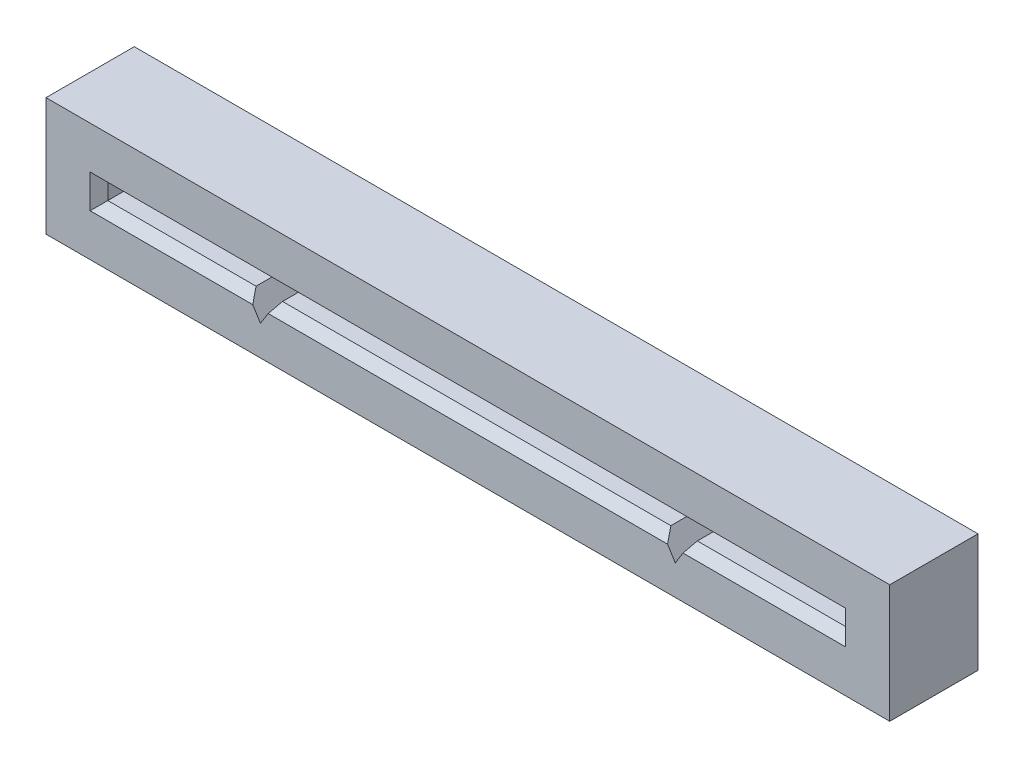
SolidWorks part; units mm, degrees
material "Сосна"
ref_plane "Front" through (0, 0, 0) normal (0, 0, 1) x (1, 0, 0)
ref_plane "Top" through (0, 0, 0) normal (0, 1, 0) x (1, 0, 0)
ref_plane "Right" through (0, 0, 0) normal (1, 0, 0) x (0, 0, -1)
sketch "Эскиз1" plane through (0, 66.7543, 0) normal (0, 0, 1) x (-1, 0, 0)
  line L1 (23.9, 63.4043) -> (-23.9, 70.1043) construction
  line L31 (-23.9, 63.4043) -> (23.9, 63.4043)
  line L32 (-23.9, 63.4043) -> (-23.9, 70.1043)
  line L33 (-23.9, 70.1043) -> (23.9, 70.1043)
  line L34 (23.9, 63.4043) -> (23.9, 70.1043)
  line L35 (-23.9, 63.4043) -> (23.9, 70.1043) construction
  point P12 (0, 66.7543)
  point P22 (0, 66.7543)
  point P26 (0, 66.7543)
  dimension "D1" = 6.7
  dimension "D2" = 47.8
extrude "Бобышка-Вытянуть1" add sketch "Эскиз1" along normal blind 5
sketch "Эскиз6" plane through (0, 66.7543, 5) normal (0, 0, 1) x (-1, 0, 0)
  line L0 (0, 66.3043) -> (0, 67.2043) construction
  line L1 (-20.9, 67.2043) -> (-12.5, 67.2043)
  line L4 (-20.9, 67.2043) -> (-20.9, 66.3043)
  line L5 (-20.9, 66.3043) -> (20.9, 66.3043)
  line L6 (20.9, 67.2043) -> (20.9, 66.3043)
  line L7 (-20.9, 67.2043) -> (20.9, 66.3043) construction
  line L8 (-20.9, 66.3043) -> (20.9, 67.2043) construction
  line L22 (20.9, 67.2043) -> (-20.9, 67.2043) construction
  line L23 (-12.5, 67.2043) -> (-11.75, 68.4043)
  line L24 (-11.75, 68.4043) -> (-11, 67.2043)
  line L25 (-11, 67.2043) -> (11, 67.2043)
  line L26 (11, 67.2043) -> (11.75, 68.4043)
  line L27 (11.75, 68.4043) -> (12.5, 67.2043)
  line L28 (12.5, 67.2043) -> (20.9, 67.2043)
  line L29 (0, 63.4043) -> (0, 70.1043) construction
  line L30 (-23.9, 63.4043) -> (23.9, 63.4043) construction
  line L31 (23.9, 70.1043) -> (-23.9, 70.1043) construction
  point P2 (0, 67.2043)
  point P6 (0, 66.7543)
  point P11 (0, 66.7543)
  point P21 (0, 0)
  dimension "D1" = 41.8
  dimension "D2" = 0.9
  dimension "D3" = 1.5
  dimension "D5" = 1.2
  dimension "D6" = 23.5
extrude "Вырез-Вытянуть1" cut sketch "Эскиз6" against normal blind 7.5
chamfer "Фаска1" distance 0.5 angle 45 6 edges at (16.7, -0.45, 5) (20.9, 0, 5) (0, 0.45, 5) (-20.9, 0, 5) (-16.7, -0.45, 5) (0, -0.45, 5)
